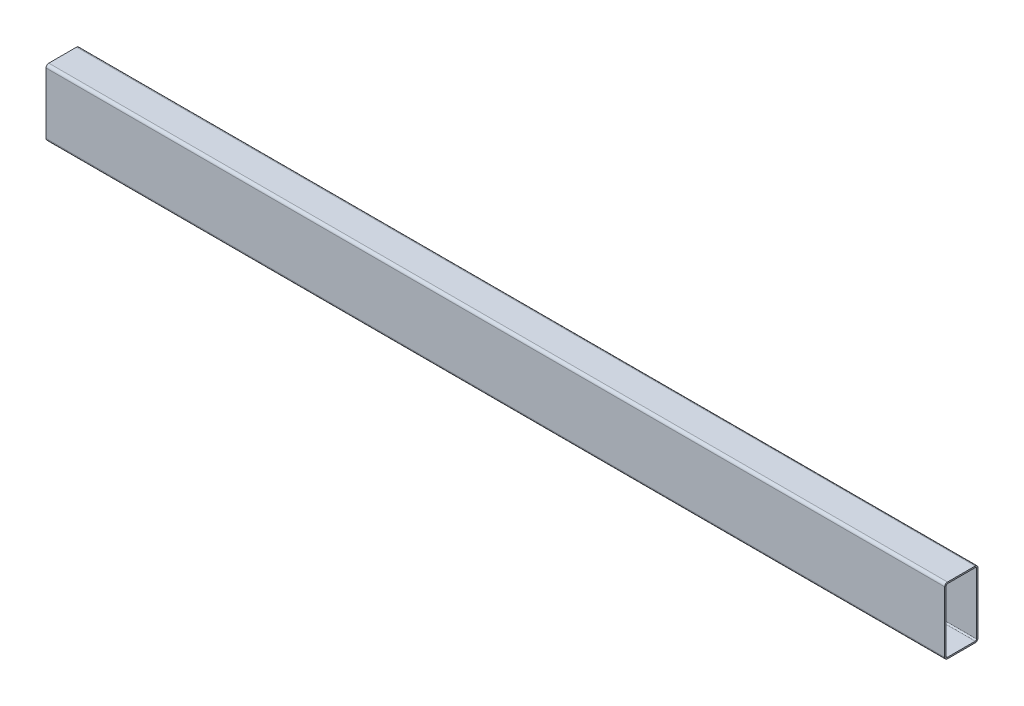
SolidWorks part; units mm, degrees
material "Plain Carbon Steel"
ref_plane "Front Plane" through (0, 0, 0) normal (0, 0, 1) x (1, 0, 0)
ref_plane "Top Plane" through (0, 0, 0) normal (0, 1, 0) x (1, 0, 0)
ref_plane "Right Plane" through (0, 0, 0) normal (1, 0, 0) x (0, 0, -1)
sketch "Sketch1" plane through (0, 0, 0) normal (1, 0, 0) x (0, 0, -1)
  line L1 (-9.4971, -10.2658) -> (22.2529, -10.2658)
  line L2 (-12.6721, -7.0908) -> (-12.6721, 62.7592)
  line L3 (-9.4971, 65.9342) -> (22.2529, 65.9342)
  line L4 (25.4279, -7.0908) -> (25.4279, 62.7592)
  arc A0 (-12.6721, 62.7592) -> (-9.4971, 65.9342) centre (-9.4971, 62.7592) cw
  arc A1 (-12.6721, -7.0908) -> (-9.4971, -10.2658) centre (-9.4971, -7.0908) ccw
  arc A2 (22.2529, -10.2658) -> (25.4279, -7.0908) centre (22.2529, -7.0908) ccw
  arc A3 (25.4279, 62.7592) -> (22.2529, 65.9342) centre (22.2529, 62.7592) ccw
  point P6 (-12.6721, 65.9342)
  point P11 (25.4279, -10.2658)
  point P14 (25.4279, 65.9342)
  dimension "D3" = 3.175
  dimension "D1" = 76.2
  dimension "D2" = 38.1
extrude "Extrude-Thin2" add sketch "Sketch1" along normal blind 1028.7 thin contours L2 A0 L3 A3 L4 A2 L1 A1 thin type one direction reverse wall 1.651
